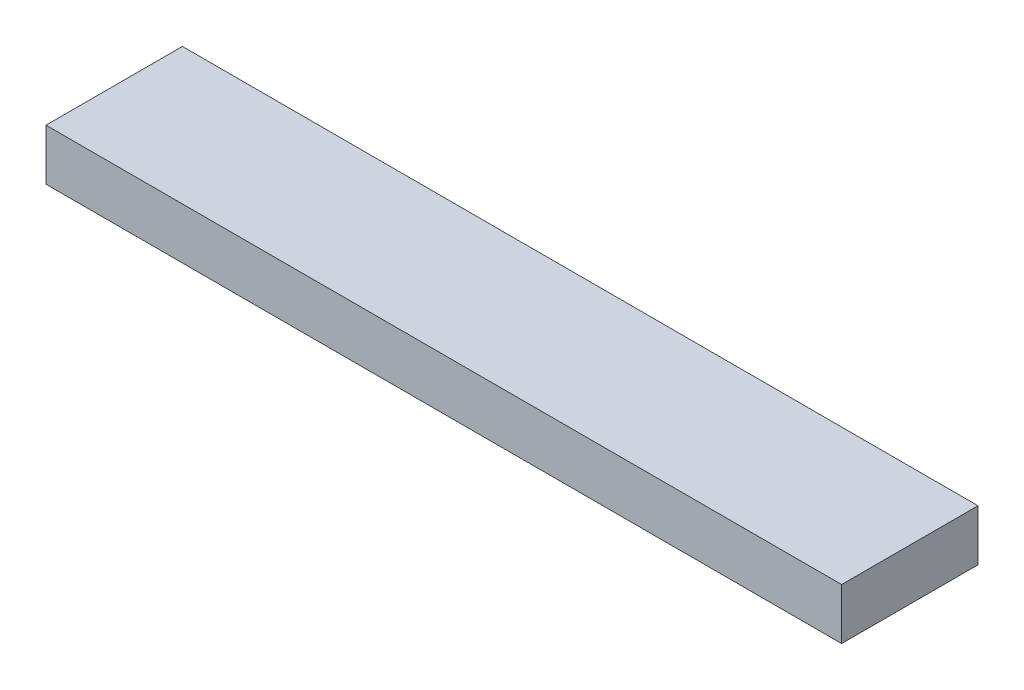
SolidWorks part; units mm, degrees
ref_plane "前视基准面" through (0, 0, 0) normal (0, 0, 1) x (1, 0, 0)
ref_plane "上视基准面" through (0, 0, 0) normal (0, 1, 0) x (1, 0, 0)
ref_plane "右视基准面" through (0, 0, 0) normal (1, 0, 0) x (0, 0, -1)
other "Configuration Table"
sketch "草图1" plane through (0, 0, 0) normal (0, 1, 0) x (1, 0, 0)
  line L1 (0, 0) -> (70, 0)
  line L2 (0, 0) -> (0, 12)
  line L3 (0, 12) -> (70, 12)
  line L4 (70, 0) -> (70, 12)
  dimension "D1" = 70
  dimension "D2" = 12
extrude "凸台-拉伸1" add sketch "草图1" along normal blind 4.5
